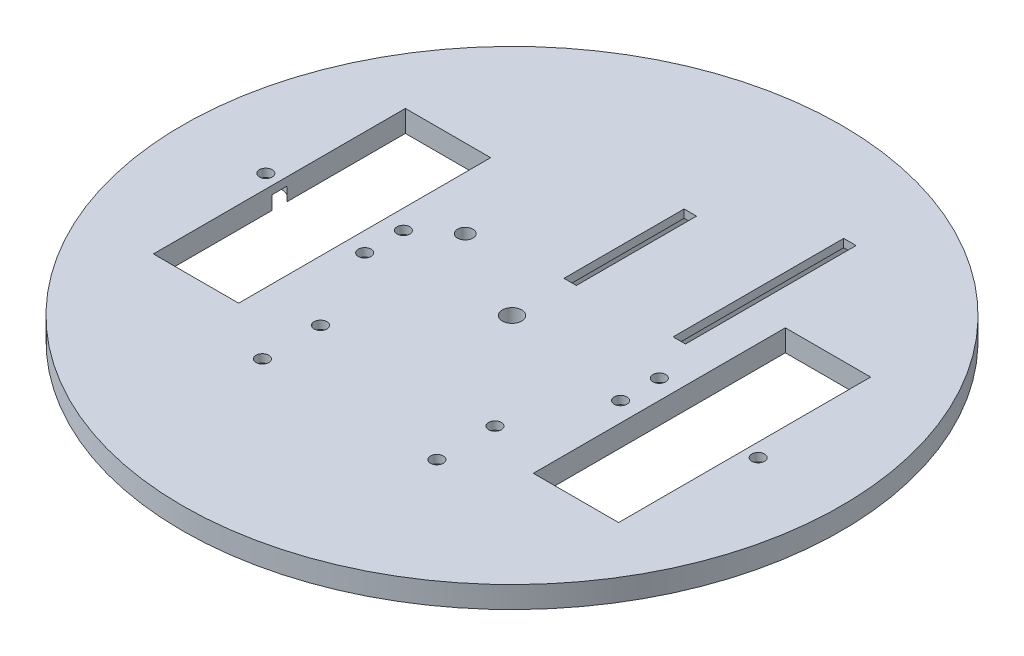
SolidWorks part; units mm, degrees
material "Delrin 2700 NC010, Low Viscosity Acetal Copolymer (SS)"
ref_plane "Front Plane" through (0, 0, 0) normal (0, 0, 1) x (1, 0, 0)
ref_plane "Top Plane" through (0, 0, 0) normal (0, 1, 0) x (1, 0, 0)
ref_plane "Right Plane" through (0, 0, 0) normal (1, 0, 0) x (0, 0, -1)
sketch "Sketch1" plane through (0, 0, 0) normal (0, 1, 0) x (1, 0, 0)
  line L0 (0, 85) -> (0, -85) construction
  line L1 (0, 0) -> (43.2628, 0) construction
  line L2 (-60, -32.5) -> (-38, -32.5)
  line L3 (60, 32.5) -> (38, 32.5)
  line L4 (60, 32.5) -> (60, -32.5)
  line L5 (60, -32.5) -> (38, -32.5)
  line L6 (38, 32.5) -> (38, -32.5)
  line L7 (60, 32.5) -> (38, -32.5) construction
  line L8 (60, -32.5) -> (38, 32.5) construction
  line L9 (-38, 32.5) -> (-38, -32.5)
  line L10 (-60, 32.5) -> (-38, 32.5)
  line L11 (-60, 32.5) -> (-60, -32.5)
  line L12 (-60, -32.5) -> (-38, 32.5) construction
  line L13 (-60, 32.5) -> (-38, -32.5) construction
  circle A0 centre (0, 0) radius 85
  circle A1 centre (0, 0) radius 71 construction
  circle A3 centre (0, 0) radius 2.5
  circle A4 centre (-24.3172, 12.25) radius 2
  point P4 (49, 0)
  point P18 (-49, 0)
  dimension "D1" = 170
  dimension "D2" = 76
  dimension "D4" = 5
  dimension "D5" = 22
  dimension "D3" = 14
  dimension "D6" = 65
  dimension "D7" = 12.25
extrude "Boss-Extrude1" add sketch "Sketch1" along normal blind 5.588
hole_wizard "CBORE for M3 SHCS1" positions "Sketch2" profile "Sketch3" counterbore size "M3" standard "ANSI Metric" end condition through all
sketch "Sketch2" plane through (0, 0, 0) normal (0, -1, 0) x (-1, 0, 0)
  line L0 (0, 0) -> (-38, 0) construction
  line L3 (0, 0) -> (0, 85) construction
  line L5 (-38, 0) -> (-85, 0) construction
  line L6 (-60, -32.5) -> (-60, 32.5) construction
  line L7 (-38, 32.5) -> (-38, -32.5) construction
  circle A0 centre (0, 0) radius 85 construction
  point P0 (-33, 5)
  point P19 (-33, -5)
  point P21 (33, 5)
  point P22 (33, -5)
  point P23 (-63.5, 0)
  point P28 (63.5, 0)
  dimension "D1" = 10
  dimension "D2" = 3.5
  dimension "D3" = 5
sketch "Sketch3" plane through (33, 0, -5) normal (1, 0, 0) x (0, 0, -1)
  line L0 (0, 0) -> (0, 5.588)
  line L1 (0, 5.588) -> (1.65, 5.588)
  line L3 (1.65, 5.588) -> (1.65, 3.5)
  line L4 (1.65, 3.5) -> (4, 3.5)
  line L5 (4, 3.5) -> (4, 0)
  line L7 (4, 0) -> (0, 0)
  line L11 (0, -6.35) -> (0, 107.95) construction
  dimension "Thru Hole Dia." = 3.3
  dimension "Thru Hole Depth" = 5.588
  dimension "C'Bore Dia." = 8
  dimension "C'Bore Depth" = 3.5
hole_wizard "CBORE for M3 SHCS2" positions "Sketch5" profile "Sketch6" counterbore size "M3" standard "ANSI Metric" end condition through all
sketch "Sketch5" plane through (0, 0, 0) normal (0, -1, 0) x (-1, 0, 0)
  line L0 (0, 0) -> (0, -85) construction
  line L3 (0, -43.6871) -> (-33, -43.6871) construction
  circle A0 centre (0, 0) radius 85 construction
  point P0 (22.5, -26.8871)
  point P12 (-22.5, -26.8871)
  point P33 (22.5, -41.8871)
  point P34 (-22.5, -41.8871)
  dimension "D1" = 45
  dimension "D2" = 16.8
  dimension "D3" = 54.75
  dimension "D4" = 10.5
  dimension "D5" = 2
sketch "Sketch6" plane through (-22.5, 0, 26.8871) normal (1, 0, 0) x (0, 0, -1)
  line L0 (0, 0) -> (0, 5.588)
  line L1 (0, 5.588) -> (1.65, 5.588)
  line L3 (1.65, 5.588) -> (1.65, 3.5)
  line L4 (1.65, 3.5) -> (4, 3.5)
  line L5 (4, 3.5) -> (4, 0)
  line L7 (4, 0) -> (0, 0)
  line L11 (0, -6.35) -> (0, 107.95) construction
  dimension "Thru Hole Dia." = 3.3
  dimension "Thru Hole Depth" = 5.588
  dimension "C'Bore Dia." = 8
  dimension "C'Bore Depth" = 3.5
sketch "Sketch16" plane through (0, 0, 0) normal (0, -1, 0) x (1, 0, 0)
  line L0 (0, 0) -> (85, 0) construction
  line L2 (0, -85) -> (0, 85) construction
  circle A0 centre (0, 0) radius 85 construction
  circle A1 centre (0, -65) radius 1.65
  circle A2 centre (0, 65) radius 1.65
  dimension "D1" = 3.3
  dimension "D2" = 65
extrude "Cut-Extrude1" cut sketch "Sketch16" against normal blind 1
sketch "Sketch17" plane through (0, 0, 0) normal (0, -1, 0) x (1, 0, 0)
  line L1 (28.75, -60) -> (25.55, -60)
  line L2 (28.75, -60) -> (28.75, -16)
  line L3 (28.75, -16) -> (25.55, -16)
  line L4 (25.55, -60) -> (25.55, -16)
  line L5 (28.75, -60) -> (25.55, -16) construction
  line L6 (28.75, -16) -> (25.55, -60) construction
  line L7 (0, 0) -> (0, -85) construction
  line L9 (38, -32.5) -> (38, 32.5) construction
  line L17 (1.6, -46) -> (-1.6, -46)
  line L18 (1.6, -46) -> (1.6, -15)
  line L19 (1.6, -15) -> (-1.6, -15)
  line L20 (-1.6, -46) -> (-1.6, -15)
  line L21 (1.6, -46) -> (-1.6, -15) construction
  line L22 (1.6, -15) -> (-1.6, -46) construction
  circle A0 centre (0, 0) radius 85 construction
  point P0 (27.15, -38)
  point P9 (0, -30.5)
  dimension "D1" = 3.2
  dimension "D2" = 16
  dimension "D3" = 60
  dimension "D4" = 10.85
  dimension "D5" = 3.2
  dimension "D6" = 46
  dimension "D7" = 15
extrude "Cut-Extrude2" cut sketch "Sketch17" against normal through all
sketch "Sketch20" plane through (0, 0, 0) normal (0, 1, 0) x (-1, 0, 0)
  line L0 (-38, -32.5) -> (-38, 32.5) construction
  line L1 (-24.15, -63) -> (-30.15, -63)
  line L2 (-24.15, -63) -> (-24.15, -13)
  line L3 (-24.15, -13) -> (-30.15, -13)
  line L4 (-30.15, -63) -> (-30.15, -13)
  line L5 (-24.15, -63) -> (-30.15, -13) construction
  line L6 (-24.15, -13) -> (-30.15, -63) construction
  line L7 (0, 0) -> (0, -85) construction
  line L17 (3, -49) -> (-3, -49)
  line L18 (3, -49) -> (3, -12)
  line L19 (3, -12) -> (-3, -12)
  line L20 (-3, -49) -> (-3, -12)
  line L21 (3, -49) -> (-3, -12) construction
  line L22 (3, -12) -> (-3, -49) construction
  point P0 (-27.15, -38)
  point P9 (0, -30.5)
  dimension "D1" = 6
  dimension "D2" = 13
  dimension "D3" = 63
  dimension "D4" = 10.85
  dimension "D5" = 6
  dimension "D6" = 49
  dimension "D7" = 12
extrude "Cut-Extrude6" cut sketch "Sketch20" along normal blind 3.5
